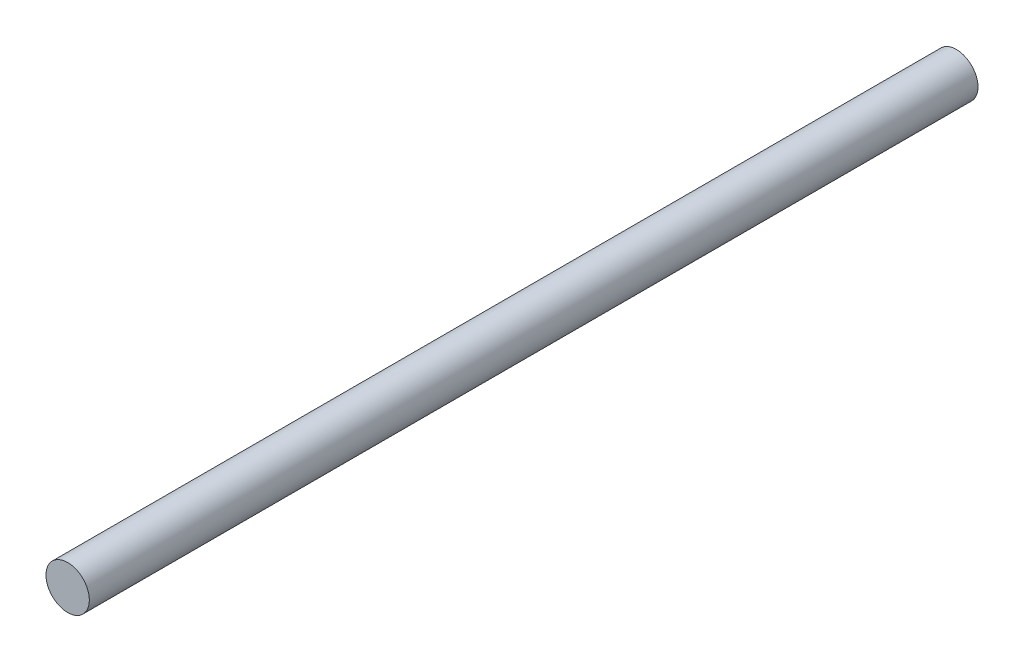
SolidWorks part; units mm, degrees
ref_plane "Front Plane" through (0, 0, 0) normal (0, 0, 1) x (1, 0, 0)
ref_plane "Top Plane" through (0, 0, 0) normal (0, 1, 0) x (1, 0, 0)
ref_plane "Right Plane" through (0, 0, 0) normal (1, 0, 0) x (0, 0, -1)
sketch "Sketch1" plane through (0, 0, 0) normal (0, 0, 1) x (1, 0, 0)
  circle A0 centre (0, 0) radius 2.44
  dimension "D1" = 4.88
extrude "Boss-Extrude1" add sketch "Sketch1" along normal blind 100
